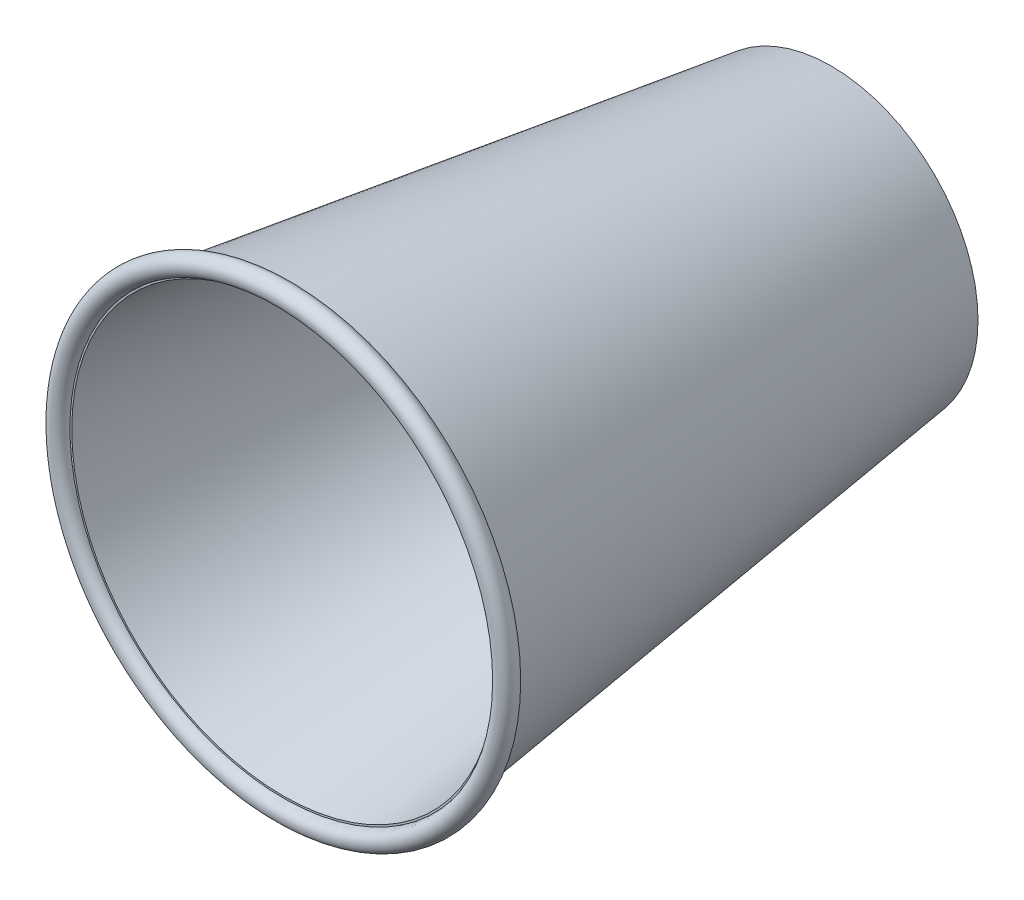
SolidWorks part; units mm, degrees
ref_plane "Front Plane" through (0, 0, 0) normal (1, 0, 0) x (0, 1, 0)
ref_plane "Top Plane" through (0, 0, 0) normal (0, 0, 1) x (0, 1, 0)
ref_plane "Right Plane" through (0, 0, 0) normal (0, 1, 0) x (-1, 0, 0)
sketch "Sketch1" plane through (0, 0, 0) normal (0, 1, 0) x (-1, 0, 0)
  line L0 (0, 3) -> (-27.6, 3)
  line L1 (-27.6, 3) -> (-27.6, 0)
  line L2 (-27.6, 0) -> (-29.573, 0)
  line L3 (-29.573, 0) -> (-44.6161, 110.4)
  line L4 (-44.6161, 110.4) -> (-42.6354, 110.4)
  line L5 (-42.6354, 110.4) -> (-28.2304, 5)
  line L6 (-28.2304, 5) -> (0, 5)
  line L7 (0, 5) -> (0, 3)
  line L8 (0, -50) -> (0, 150) construction
revolve "Cup" add sketch "Sketch1" angle 360 about L8
sketch "Sketch2" plane through (0, 0, 0) normal (0, 1, 0) x (-1, 0, 0)
  line L0 (0, -50) -> (0, 150) construction
  circle A0 centre (-45, 110.4) radius 2
revolve "BeadRound" add sketch "Sketch2" angle 360 about L0
sketch "Sketch3" plane through (0, 0, 0) normal (0, 1, 0) x (-1, 0, 0)
  line L0 (-44.3436, 108.4) -> (-47, 110)
  line L1 (-47, 110) -> (-45.8, 112.4)
  line L2 (-45.8, 112.4) -> (-42.5, 111.6)
  line L3 (-42.5, 111.6) -> (-42.45, 110)
  line L4 (-42.45, 110) -> (-44.3436, 108.4)
  line L5 (0, -50) -> (0, 150) construction
revolve "BeadCollision" [suppressed] add sketch "Sketch3" angle 360 about L5
